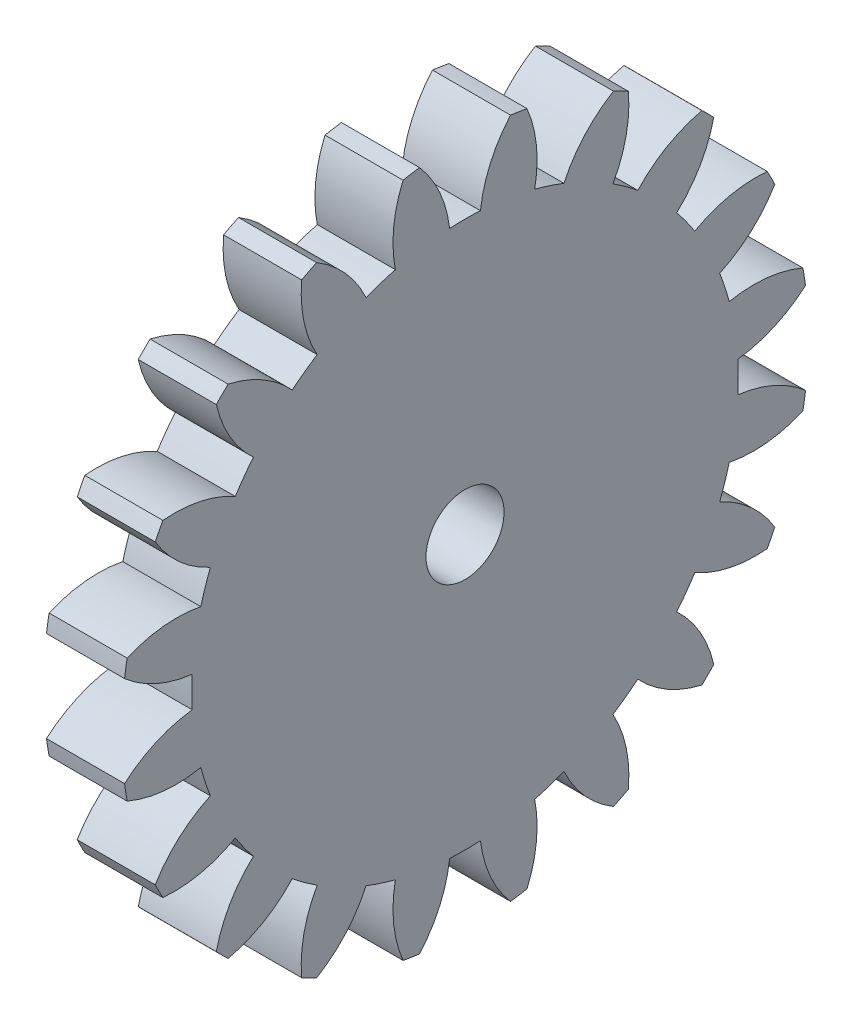
SolidWorks part; units mm, degrees
ref_plane "Plane1" through (0, 0, 0) normal (0, 0, 1) x (1, 0, 0)
ref_plane "Plane2" through (0, 0, 0) normal (0, 1, 0) x (1, 0, 0)
ref_plane "Plane3" through (0, 0, 0) normal (1, 0, 0) x (0, 0, -1)
sketch "HoldingSke" plane through (0, 0, 0) normal (0, 1, 0) x (1, 0, 0)
  line L0 (0, 0) -> (0.4698, -0.171)
  line L1 (-15, 0) -> (100, 0) construction
  line L2 (0, 0) -> (-2.1039, 2.3779)
  line L3 (0, 0) -> (-11.863, 4.5341)
  line L4 (0, 0) -> (8.1152, 2.9537)
  line L5 (0, 0) -> (-9.3695, -3.4946)
  line L6 (0, 0) -> (-4.1448, -2.7965)
  line L7 (-2.1039, 2.3779) -> (0.0486, 12.1435)
  line L8 (-76.2, 54.61) -> (-75.3, 54.61)
  line L9 (-71.009, 38.7566) -> (-53.1078, 45.2721)
  line L10 (-76.2, 71.12) -> (104.1128, 71.12)
  line L11 (0, 0) -> (-5, 0)
  line L12 (-76.2, 101.6) -> (-76.133, 101.6)
  line L13 (24.9733, 27.94) -> (52.9518, 28.4284)
  line L14 (24.9733, 27.94) -> (24.9743, 27.94)
  line L15 (24.9733, 27.94) -> (100.4006, 29.5858)
  line L16 (-63.627, -2) -> (-12.827, -2)
  circle A0 centre (0, 0) radius 2.5
  circle A1 centre (0, 0) radius 3
  circle A2 centre (0, 0) radius 3
  circle A3 centre (0, 0) radius 2.5
  dimension "Bore" = 5
  dimension "MBD" = 5
  dimension "Num_teeth" = 20
  dimension "Pitch" = 0.5
  dimension "Show_teeth" = 20
  dimension "Thickness" = 5
  dimension "Ap" = 20
  dimension "H" = 19.05
  dimension "Pitch_radius" = 180.3128
  dimension "Width" = 5
  dimension "Backlash" = 0.067
  dimension "Addendum_fac" = 1
  dimension "Dedendum_fac" = 1.25
  dimension "Clearance_fac" = 0.25
  dimension "Dedendum_add" = 0.001
  dimension "Module" = 2
sketch "BasProSke" plane through (0, 0, 0) normal (0, 1, 0) x (1, 0, 0)
  line L0 (-10, 0) -> (60, 0) construction
  line L1 (0, 0) -> (0, 22)
  line L2 (0, 0) -> (5, 0)
  line L3 (5, 0) -> (5, 22)
  line L4 (5, 22) -> (0, 22)
  dimension "Thickness" = 5
  dimension "Diameter" = 44
revolve "Base-Revolve" add sketch "BasProSke" angle 360 about L0
sketch "TooCutSke" plane through (0, 0, 0) normal (1, 0, 0) x (0, 0, -1)
  line L1 (0, 0) -> (0, 107) construction
  line L2 (0, 0) -> (-1.6864, 19.9288) construction
  line L3 (0, 0) -> (-6.2409, 39.4033) construction
  line L4 (-1.6864, 19.9288) -> (-3.1204, 19.7016) construction
  arc A0 (0.9862, 17.4712) -> (-0.9862, 17.4712) centre (0, 0) ccw
  arc A1 (2.9329, 21.8293) -> (-2.9329, 21.8293) centre (0, 0) ccw
  circle A2 centre (0, 0) radius 20 construction
  circle A3 centre (0, 0) radius 18.7939 construction
  arc A4 (-0.9862, 17.4712) -> (-2.9329, 21.8293) centre (-8.9313, 16.536) ccw
  arc A5 (2.9329, 21.8293) -> (0.9862, 17.4712) centre (8.9313, 16.536) ccw
  dimension "Root_dia" = 34.998
  dimension "Overcut_dia" = 44.0508
  dimension "Pitch_dia" = 40
  dimension "Base_dia" = 37.5877
  dimension "Flank_rad" = 8
  dimension "Half_ang" = 9
  dimension "Half_CT" = 1.4519
extrude "ToothCut" cut sketch "TooCutSke" along normal through all
fillet "Breaks" [suppressed] radius 0.04
fillet "RootFillets" [suppressed] radius 0.501
pattern_circular "TeethCuts" count 20 every 18 about axis through (-10, 0, 0) along (1, 0, 0) of "ToothCut", "RootFillets", "Breaks"
sketch "HubNeaOneSke" plane through (0, 0, 0) normal (-1, 0, 0) x (0, 0, 1)
  circle A0 centre (0, 0) radius 3
extrude "HubNearOne" add sketch "HubNeaOneSke" along normal blind 5.0001
sketch "HubNeaBotSke" plane through (0, 0, 0) normal (-1, 0, 0) x (0, 0, 1)
  circle A0 centre (0, 0) radius 3
extrude "HubNearBoth" [suppressed] add sketch "HubNeaBotSke" along normal blind 2.5
ref_plane "FarPln" through (5, 0, 0) normal (1, 0, 0) x (0, 0, -1)
sketch "HubFarSke" plane through (5, 0, 0) normal (1, 0, 0) x (0, 0, -1)
  circle A0 centre (0, 0) radius 3
extrude "HubFar" [suppressed] add sketch "HubFarSke" along normal blind 2.5
sketch "BorSke" plane through (0, 0, 0) normal (1, 0, 0) x (0, 0, -1)
  circle A0 centre (0, 0) radius 2.5
  dimension "Diameter" = 5
extrude "Bore" cut sketch "BorSke" along normal mid plane 20.0001
sketch "KeySke" plane through (0, 0, 0) normal (1, 0, 0) x (0, 0, -1)
  line L0 (-1, 0) -> (-1, 3.4)
  line L1 (-1, 3.4) -> (1, 3.4)
  line L2 (1, 3.4) -> (1, 0)
  line L3 (0, 0) -> (0, 34) construction
  line L4 (-1, 0) -> (1, 0)
extrude "Keyway" [suppressed] cut sketch "KeySke" along normal mid plane 20.0001
pattern_circular "Keyway2" [suppressed] count 2 every 90 about axis through (-10, 0, 0) along (1, 0, 0)
equation "' \"Module@HoldingSke\" = 6.35"
equation "' \"Num_teeth@HoldingSke\" = 12"
equation "' \"Ap@HoldingSke\" =  20"
equation "' \"Ap@HoldingSke\" = 20"
equation "' \"Width@HoldingSke\" = 0.5 * 25.4"
equation "' \"Hub_dia@HoldingSke\"= 1 * 25.4"
equation "' \"Hub_dia@HoldingSke\" = 1 * 25.4"
equation "' \"Overall_len@HoldingSke\" = 1.0 * 25.4"
equation "' \"Bore@HoldingSke\" = 0.75 * 25.4"
equation "' \"T_dim@HoldingSke\" = 0.1 * 25.4"
equation "' \"Width@KeySke\" = 0.25 * 25.4"
equation "' \"Show_teeth@HoldingSke\" = 13"
equation "' \"Backlash@HoldingSke\" = 0.009 * 25.4"
equation "' \"Addendum_fac@HoldingSke\" = 1.0"
equation "' \"Dedendum_fac@HoldingSke\" = 1.25"
equation "' \"Dedendum_add@HoldingSke\" = 0.00005 * 25.4"
equation "' \"Clearance_fac@HoldingSke\" = 0.25"
equation "\"Pitch@HoldingSke\" = 1 / \"Module@HoldingSke\""
equation "\"Overcut_dia@TooCutSke\" = (\"Num_teeth@HoldingSke\" + 2 * \"Addendum_fac@HoldingSke\") / \"Pitch@HoldingSke\" + 0.002 * 25.4"
equation "\"Pitch_dia@TooCutSke\" = \"Num_teeth@HoldingSke\" / \"Pitch@HoldingSke\""
equation "\"Base_dia@TooCutSke\" = \"Num_teeth@HoldingSke\" / \"Pitch@HoldingSke\" * cos((\"Ap@HoldingSke\"  * 3.14159265 / 180))"
equation "\"Root_dia@TooCutSke\" = (\"Num_teeth@HoldingSke\" + 2) / \"Pitch@HoldingSke\" - 2 * (\"Addendum_fac@HoldingSke\" + \"Dedendum_fac@HoldingSke\") / \"Pitch@HoldingSke\" - \"Dedendum_add@HoldingSke\" * 2"
equation "\"Half_ang@TooCutSke\" = 180 / \"Num_teeth@HoldingSke\""
equation "\"Half_CT@TooCutSke\" = \"Num_teeth@HoldingSke\" / \"Pitch@HoldingSke\" * sin((3.14159265 / 2 / \"Num_teeth@HoldingSke\")) / 2 - 7 * \"Backlash@HoldingSke\" / 4"
equation "\"Flank_rad@TooCutSke\" = \"Num_teeth@HoldingSke\" / \"Pitch@HoldingSke\" / 5"
equation "\"Radius@RootFillets\" = \"Clearance_fac@HoldingSke\" / \"Pitch@HoldingSke\" + \"Dedendum_add@HoldingSke\""
equation "\"Break_rad@Breaks\" = 0.02 / \"Pitch@HoldingSke\""
equation "\"Thickness@HoldingSke\" = \"Width@HoldingSke\""
equation "\"OAL@HoldingSke\" = \"Thickness@HoldingSke\""
equation "\"MHD@HoldingSke\" = (\"Num_teeth@HoldingSke\" + 2) / \"Pitch@HoldingSke\" - 2 * (\"Addendum_fac@HoldingSke\" + \"Dedendum_fac@HoldingSke\")  / \"Pitch@HoldingSke\" - \"Dedendum_add@HoldingSke\" * 2"
equation "\"MBD@HoldingSke\" = (\"Num_teeth@HoldingSke\" + 2) / \"Pitch@HoldingSke\" - 2 * (\"Addendum_fac@HoldingSke\" + \"Dedendum_fac@HoldingSke\")  / \"Pitch@HoldingSke\" - \"Dedendum_add@HoldingSke\" * 2 - 0.002 * 25.4"
equation "\"MHD@HoldingSke\" = ((sgn( \"MHD@HoldingSke\" - \"Hub_dia@HoldingSke\" )-1)*( \"MHD@HoldingSke\" - \"Hub_dia@HoldingSke\" ))/-2+ \"Hub_dia@HoldingSke\""
equation "\"MBD@HoldingSke\" = ((sgn( \"MBD@HoldingSke\" - \"Bore@HoldingSke\" )-1)*( \"MBD@HoldingSke\" - \"Bore@HoldingSke\" ))/-2+ \"Bore@HoldingSke\""
equation "\"OAL@HoldingSke\" = ((sgn( \"OAL@HoldingSke\" - \"Overall_len@HoldingSke\" )+1)*( \"OAL@HoldingSke\" - \"Overall_len@HoldingSke\" ))/2 + \"Overall_len@HoldingSke\" + 0.000002 * 25.4"
equation "\"Num_teeth@TeethCuts\" = int( \"Show_teeth@HoldingSke\" ) + 1"
equation "\"Num_teeth@TeethCuts\" = ((sgn( \"Num_teeth@TeethCuts\" - \"Num_teeth@HoldingSke\" )-1)*( \"Num_teeth@TeethCuts\" - \"Num_teeth@HoldingSke\" ))/-2+ \"Num_teeth@HoldingSke\""
equation "\"Num_teeth@TeethCuts\" = ((sgn( \"Num_teeth@TeethCuts\" - 2.0)+1)*( \"Num_teeth@TeethCuts\" - 2.0))/2 +2.0"
equation "\"Angle@TeethCuts\" = 360.0 / \"Num_teeth@HoldingSke\""
equation "\"Diameter@BasProSke\" = (\"Num_teeth@HoldingSke\" + 2 * \"Addendum_fac@HoldingSke\") / \"Pitch@HoldingSke\""
equation "\"Thickness@BasProSke\"  = \"Thickness@HoldingSke\""
equation "' \"Fillet_rad@BasProSke\" =  \"Thickness@HoldingSke\" * 0.05"
equation "' \"Fillet_rad@BasProSke\" = \"Thickness@HoldingSke\" * 0.05"
equation "\"MHD@HoldingSke\" = ((sgn( \"MHD@HoldingSke\" - \"Root_dia@TooCutSke\" )-1)*( \"MHD@HoldingSke\" - \"Root_dia@TooCutSke\" ))/-2+ \"Root_dia@TooCutSke\""
equation "\"Diameter@HubNeaOneSke\" = \"MHD@HoldingSke\""
equation "\"Length@HubNearOne\" = \"OAL@HoldingSke\" - \"Thickness@BasProSke\""
equation "\"Diameter@HubNeaBotSke\" = \"MHD@HoldingSke\""
equation "\"Length@HubNearBoth\" = ( \"OAL@HoldingSke\" - \"Thickness@BasProSke\" ) / 2.0"
equation "\"Thickness@FarPln\" = \"Thickness@BasProSke\""
equation "\"Diameter@HubFarSke\" = \"MHD@HoldingSke\""
equation "\"Length@HubFar\" = ( \"OAL@HoldingSke\" - \"Thickness@BasProSke\" ) / 2.0"
equation "\"Diameter@BorSke\" = \"MBD@HoldingSke\""
equation "\"D1@Bore\" = \"OAL@HoldingSke\" * 2.0"
equation "\"D1@Keyway\" = \"OAL@HoldingSke\" * 2.0"
equation "\"Offset@KeySke\" = \"T_dim@HoldingSke\" + \"MBD@HoldingSke\" / 2.0"
